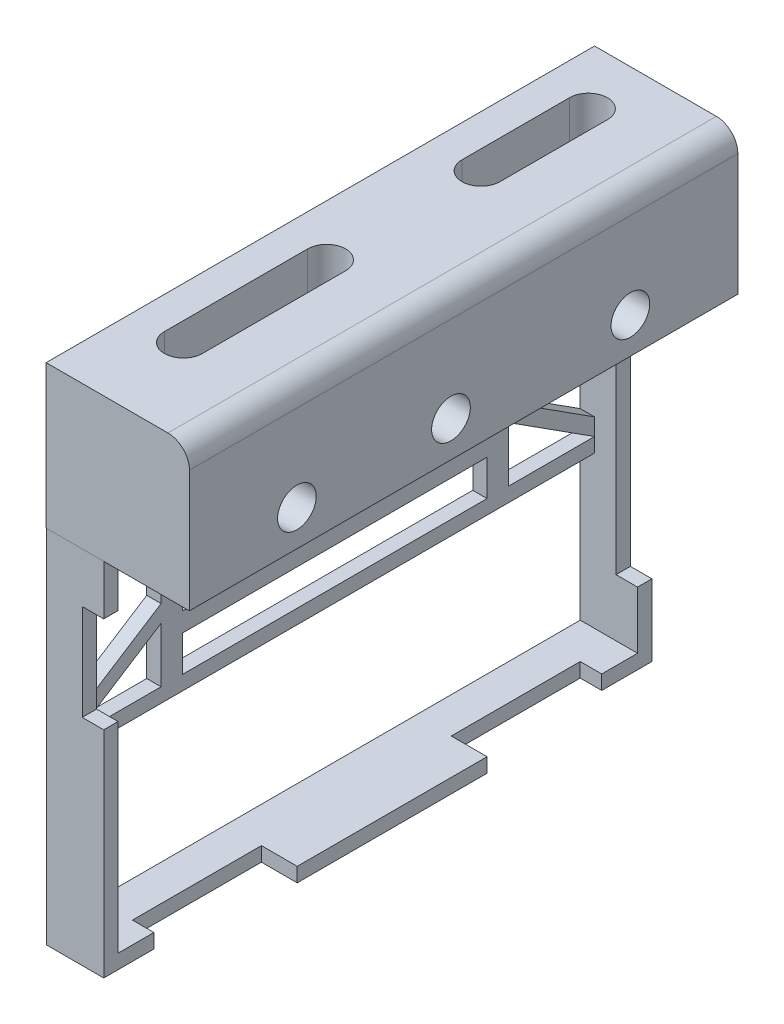
SolidWorks part; units mm, degrees
ref_plane "前视基准面" through (0, 0, 0) normal (0, 0, 1) x (1, 0, 0)
ref_plane "上视基准面" through (0, 0, 0) normal (0, 1, 0) x (1, 0, 0)
ref_plane "右视基准面" through (0, 0, 0) normal (1, 0, 0) x (0, 0, -1)
other "Configuration Table"
sketch "草图1" plane through (0, 0, 0) normal (1, 0, 0) x (0, 0, -1)
  line L0 (-2, 48.4) -> (74.5, 48.4)
  line L1 (0, 0) -> (72.5, 0)
  line L2 (0, 0) -> (0, 46.4)
  line L3 (0, 46.4) -> (72.5, 46.4)
  line L4 (72.5, 0) -> (72.5, 46.4)
  line L5 (74.5, -2) -> (74.5, 48.4)
  line L6 (-2, -2) -> (74.5, -2)
  line L7 (-2, -2) -> (-2, 48.4)
  dimension "D1" = 46.4
  dimension "D2" = 72.5
  dimension "D3" = 2
extrude "凸台-拉伸1" add sketch "草图1" along normal blind 3
sketch "草图2" plane through (3, 0, 0) normal (1, 0, 0) x (0, 0, -1)
  line L0 (0, 0) -> (72.5, 0) construction
  line L1 (23, 0) -> (49.5, 0)
  line L2 (23, 0) -> (23, -2)
  line L3 (23, -2) -> (49.5, -2)
  line L4 (49.5, 0) -> (49.5, -2)
  line L5 (-2, -2) -> (74.5, -2) construction
  line L6 (74.5, -2) -> (74.5, 48.4) construction
  line L7 (-2, 48.4) -> (-2, -2) construction
  line L8 (0, 46.4) -> (0, 0) construction
  line L9 (-2, -2) -> (0, -2)
  line L10 (-2, -2) -> (-2, 28)
  line L11 (-2, 28) -> (0, 28)
  line L12 (0, 0) -> (0, 28)
  line L13 (72.5, 0) -> (72.5, 46.4) construction
  line L14 (74.5, -2) -> (72.5, -2)
  line L15 (74.5, -2) -> (74.5, 8)
  line L16 (74.5, 8) -> (72.5, 8)
  line L17 (72.5, 0) -> (72.5, 8)
  line L18 (72.5, 46.4) -> (0, 46.4) construction
  line L19 (72.5, -2) -> (67.5, -2)
  line L21 (72.5, 0) -> (67.5, 0)
  line L22 (67.5, -2) -> (67.5, 0)
  line L23 (0, -2) -> (5, -2)
  line L25 (0, 0) -> (5, 0)
  line L26 (5, -2) -> (5, 0)
  line L27 (-2, 48.4) -> (5, 48.4)
  line L28 (-2, 48.4) -> (-2, 46.4)
  line L29 (0, 46.4) -> (5, 46.4)
  line L30 (5, 48.4) -> (5, 46.4)
  line L33 (-2, 46.4) -> (-2, 41.4)
  line L34 (-2, 41.4) -> (0, 41.4)
  line L35 (0, 46.4) -> (0, 41.4)
  line L36 (74.5, 48.4) -> (72.5, 48.4)
  line L37 (74.5, 48.4) -> (74.5, 41.4)
  line L38 (74.5, 41.4) -> (72.5, 41.4)
  line L39 (72.5, 48.4) -> (72.5, 41.4)
  dimension "D1" = 25
  dimension "D2" = 25
  dimension "D3" = 30
  dimension "D4" = 10
  dimension "D5" = 5
  dimension "D6" = 5
  dimension "D7" = 5
  dimension "D8" = 7
  dimension "D9" = 5
  dimension "D10" = 7
extrude "凸台-拉伸2" add sketch "草图2" along normal blind 3
sketch "草图3" plane through (0, 0, 0) normal (-1, 0, 0) x (0, 0, 1)
  line L1 (-74.5, 48.4) -> (2.0414, 48.4)
  line L2 (-74.5, 48.4) -> (-74.5, 68.4)
  line L4 (-74.5, 68.4) -> (2.0414, 68.4)
  line L5 (2.0414, 48.4) -> (2.0414, 68.4)
  circle A0 centre (-59.5, 53.4) radius 2.7
  circle A1 centre (-12.9586, 53.4) radius 2.7
  circle A2 centre (-34.4586, 53.4) radius 2.7
  dimension "D2" = 15
  dimension "D6" = 15
  dimension "D8" = 5.4
  dimension "D9" = 5.4
  dimension "D10" = 5.4
  dimension "D11" = 34.4586
  dimension "D1" = 20
  dimension "D3" = 15
  dimension "D4" = 15
  dimension "D5" = 15
  dimension "D7" = 36.5
extrude "凸台-拉伸4" add sketch "草图3" against normal blind 18 and the other way blind 2
fillet "圆角1" radius 3 1 edges at (18, 68.4, -36.2293)
sketch "草图4" plane through (0, 68.4, 0) normal (0, 1, 0) x (1, 0, 0)
  line L0 (5.15, 66.5) -> (5.15, 51.5) construction
  line L1 (7.8, 66.5) -> (7.8, 51.5)
  line L2 (2.5, 66.5) -> (2.5, 51.5)
  line L3 (5.15, 29.9586) -> (5.15, 9.9586) construction
  line L4 (7.8, 29.9586) -> (7.8, 9.9586)
  line L5 (2.5, 29.9586) -> (2.5, 9.9586)
  line L6 (-2, -2.0414) -> (-2, 74.5) construction
  line L7 (-2, -2.0414) -> (15, -2.0414) construction
  line L8 (-2, 74.5) -> (15, 74.5) construction
  arc A0 (7.8, 66.5) -> (2.5, 66.5) centre (5.15, 66.5) ccw
  arc A1 (2.5, 51.5) -> (7.8, 51.5) centre (5.15, 51.5) ccw
  arc A2 (7.8, 29.9586) -> (2.5, 29.9586) centre (5.15, 29.9586) ccw
  arc A3 (2.5, 9.9586) -> (7.8, 9.9586) centre (5.15, 9.9586) ccw
  point P2 (5.15, 59)
  point P7 (5.15, 19.9586)
  dimension "D7" = 8
  dimension "D1" = 4.5
  dimension "D2" = 20
  dimension "D3" = 5.3
  dimension "D4" = 12
  dimension "D5" = 15
  dimension "D6" = 4.5
extrude "切除-拉伸1" cut sketch "草图4" against normal blind 18
sketch "草图5" plane through (0, 0, 0) normal (-1, 0, 0) x (0, 0, 1)
  line L0 (-72.5, 23.2) -> (-60.5, 23.2)
  line L1 (-72.5, 0) -> (-72.5, 46.4) construction
  line L2 (0, 46.4) -> (0, 0) construction
  line L3 (0, 23.2) -> (-12, 30.88)
  line L4 (-72.5, 46.4) -> (0, 46.4) construction
  line L5 (-36.25, 46.4) -> (-57.5, 32.8)
  line L6 (-36.8352, 48.4) -> (-57.5, 35.1745)
  line L7 (-74.5, 21.2) -> (2, 21.2)
  line L8 (2, 24.2945) -> (-12, 33.2545)
  line L9 (-36.25, 48.7745) -> (-79.3352, 21.2) construction
  line L10 (-79.3352, 21.2) -> (6.8352, 21.2) construction
  line L11 (6.8352, 21.2) -> (-36.25, 48.7745) construction
  line L12 (-60.5, 33.2545) -> (-74.5, 24.2945)
  line L13 (2, -2) -> (2, 48.4)
  line L14 (2, 48.4) -> (-74.5, 48.4)
  line L15 (-74.5, 48.4) -> (-74.5, -2)
  line L16 (-74.5, -2) -> (2, -2)
  line L17 (2, 21.2) -> (2, 24.2945)
  line L18 (-12, 48.4) -> (-15, 48.4)
  line L19 (-74.5, 24.2945) -> (-74.5, 21.2)
  line L22 (-60.5, 23.2) -> (-60.5, 30.88)
  line L23 (-60.5, 48.4) -> (-57.5, 48.4)
  line L24 (-57.5, 23.2) -> (-57.5, 28.2)
  line L26 (-15, 23.2) -> (-15, 28.2)
  line L27 (-15, 48.4) -> (-12, 48.4)
  line L28 (-12, 23.2) -> (-12, 30.88)
  line L29 (-60.5, 30.88) -> (-72.5, 23.2)
  line L30 (-36.25, 46.4) -> (-72.5, 23.2) construction
  line L31 (-60.5, 33.2545) -> (-60.5, 48.4)
  line L32 (-57.5, 35.1745) -> (-57.5, 48.4)
  line L33 (-15, 35.1745) -> (-35.6648, 48.4)
  line L34 (-15, 32.8) -> (-36.25, 46.4)
  line L35 (0, 23.2) -> (-36.25, 46.4) construction
  line L36 (-15, 35.1745) -> (-15, 48.4)
  line L37 (-12, 33.2545) -> (-12, 48.4)
  line L38 (-57.5, 48.4) -> (-60.5, 48.4)
  line L39 (-35.6648, 48.4) -> (-36.8352, 48.4)
  line L40 (-57.5, 23.2) -> (-15, 23.2)
  line L41 (-72.5, 23.2) -> (0, 23.2) construction
  line L42 (-12, 23.2) -> (0, 23.2)
  line L43 (-57.5, 30.88) -> (-15, 30.88)
  line L44 (-15, 28.2) -> (-57.5, 28.2)
  line L45 (-57.5, 30.88) -> (-57.5, 32.8)
  line L46 (-15, 30.88) -> (-15, 32.8)
  line M15 (2, -2) -> (2, 48.4)
  line M16 (2, 48.4) -> (-74.5, 48.4)
  line M17 (-74.5, 48.4) -> (-74.5, -2)
  line M19 (-72.5, 46.4) -> (0, 46.4)
  line M20 (0, 46.4) -> (0, 0)
  line M22 (-72.5, 0) -> (-72.5, 46.4)
  dimension "D1" = 2
  dimension "D3" = 3
  dimension "D4" = 3
  dimension "D5" = 12
  dimension "D6" = 12
  dimension "D7" = 5
  dimension "D2" = 0
extrude "凸台-拉伸5" add sketch "草图5" along normal blind 2 contours L8 L7 M15 M20 | L46 L43 L45 L5 L6 L32 L31 L12 L29 L22 L0 L7 L42 L28 L3 L8 L37 L36 L33 L34 L44 L26 L40 L24 M19 M22 M20 | L37 L36 M19 M16 | L32 L31 M19 M16 | L33 L6 M19 M16 | L12 L7 M22 M17
sketch "草图6" plane through (0, 0, 0) normal (-1, 0, 0) x (0, 0, 1)
  line L0 (2, -2) -> (2, 21.2) construction
  line L1 (2, 21.2) -> (0, 21.2) construction
  line L2 (0, 21.2) -> (0, 0) construction
  line L3 (0, 0) -> (-72.5, 0) construction
  line L4 (-72.5, 0) -> (-72.5, 21.2) construction
  line L5 (-72.5, 21.2) -> (-74.5, 21.2) construction
  line L6 (0, 46.4) -> (0, 25.5745)
  line L7 (0, 25.5745) -> (2, 24.2945)
  line L8 (2, 24.2945) -> (2, 48.4)
  line L9 (2, 48.4) -> (-12, 48.4)
  line L10 (-12, 48.4) -> (-12, 46.4)
  line L11 (-12, 46.4) -> (0, 46.4)
  line L12 (0, 46.4) -> (0, 25.5745)
  line L13 (0, 25.5745) -> (2, 24.2945)
  line L14 (2, 24.2945) -> (2, 48.4)
  line L15 (2, 48.4) -> (-12, 48.4)
  line L16 (-12, 48.4) -> (-12, 46.4)
  line L17 (-12, 46.4) -> (0, 46.4)
  line L18 (-74.5, 48.4) -> (-74.5, 24.2945)
  line L19 (-74.5, 24.2945) -> (-72.5, 25.5745)
  line L20 (-72.5, 25.5745) -> (-72.5, 46.4)
  line L21 (-72.5, 46.4) -> (-60.5, 46.4)
  line L22 (-60.5, 46.4) -> (-60.5, 48.4)
  line L23 (-60.5, 48.4) -> (-74.5, 48.4)
  line L24 (-74.5, 48.4) -> (-74.5, 24.2945)
  line L25 (-74.5, 24.2945) -> (-72.5, 25.5745)
  line L26 (-72.5, 25.5745) -> (-72.5, 46.4)
  line L27 (-72.5, 46.4) -> (-60.5, 46.4)
  line L28 (-60.5, 46.4) -> (-60.5, 48.4)
  line L29 (-60.5, 48.4) -> (-74.5, 48.4)
  line L30 (-74.5, 21.2) -> (-74.5, -2) construction
  line L31 (-74.5, -2) -> (2, -2) construction
  line L32 (-15, 46.4) -> (-15, 48.4) construction
  line L33 (-15, 48.4) -> (-35.6648, 48.4) construction
  line L34 (-35.6648, 48.4) -> (-32.5398, 46.4) construction
  line L35 (-32.5398, 46.4) -> (-15, 46.4) construction
  line L36 (-57.5, 46.4) -> (-39.9602, 46.4) construction
  line L37 (-39.9602, 46.4) -> (-36.8352, 48.4) construction
  line L38 (-36.8352, 48.4) -> (-57.5, 48.4) construction
  line L39 (-57.5, 48.4) -> (-57.5, 46.4) construction
  line L40 (2, -2) -> (2, 21.2)
  line L41 (2, 21.2) -> (0, 21.2)
  line L42 (0, 21.2) -> (0, 0)
  line L43 (0, 0) -> (-72.5, 0)
  line L44 (-72.5, 0) -> (-72.5, 21.2)
  line L45 (-72.5, 21.2) -> (-74.5, 21.2)
  line L46 (-74.5, 21.2) -> (-74.5, -2)
  line L47 (-74.5, -2) -> (2, -2)
  line L48 (-15, 46.4) -> (-15, 48.4)
  line L49 (-15, 48.4) -> (-35.6648, 48.4)
  line L50 (-35.6648, 48.4) -> (-32.5398, 46.4)
  line L51 (-32.5398, 46.4) -> (-15, 46.4)
  line L52 (-57.5, 46.4) -> (-39.9602, 46.4)
  line L53 (-39.9602, 46.4) -> (-36.8352, 48.4)
  line L54 (-36.8352, 48.4) -> (-57.5, 48.4)
  line L55 (-57.5, 48.4) -> (-57.5, 46.4)
  dimension "D1" = 0
  dimension "D2" = 0
extrude "凸台-拉伸6" add sketch "草图6" along normal blind 2
sketch "草图7" plane through (6, 0, 0) normal (1, 0, 0) x (0, 0, -1)
  line L4 (23, 0) -> (23, -2)
  line L5 (23, -2) -> (49.5, -2)
  line L6 (49.5, -2) -> (49.5, 0)
  line L7 (49.5, 0) -> (23, 0)
  line L8 (23, 0) -> (23, -2)
  line L9 (23, -2) -> (49.5, -2)
  line L10 (49.5, -2) -> (49.5, 0)
  line L11 (49.5, 0) -> (23, 0)
  dimension "D1" = 0
extrude "凸台-拉伸7" add sketch "草图7" along normal blind 2
sketch "草图8" plane through (3, 0, 0) normal (1, 0, 0) x (0, 0, -1)
  line L4 (72.5, 46.4) -> (72.5, 48.4)
  line L5 (72.5, 48.4) -> (5, 48.4)
  line L6 (5, 48.4) -> (5, 46.4)
  line L7 (5, 46.4) -> (72.5, 46.4)
  line L8 (72.5, 46.4) -> (72.5, 48.4)
  line L9 (72.5, 48.4) -> (5, 48.4)
  line L10 (5, 48.4) -> (5, 46.4)
  line L11 (5, 46.4) -> (72.5, 46.4)
  dimension "D1" = 0
extrude "凸台-拉伸8" add sketch "草图8" along normal blind 10
